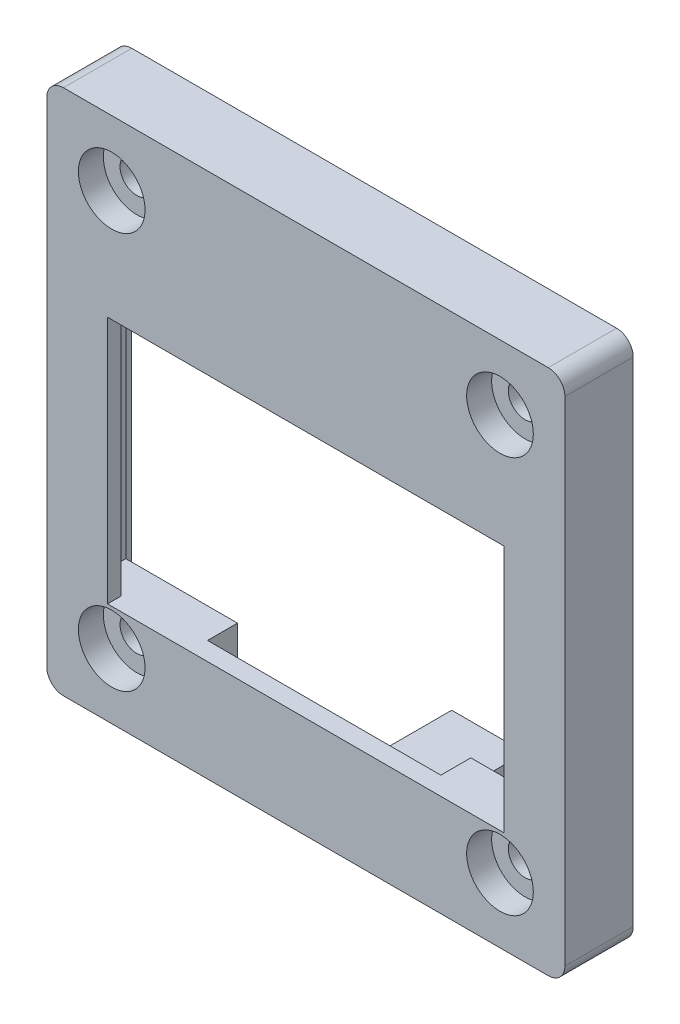
SolidWorks part; units mm, degrees
ref_plane "前视基准面" through (0, 0, 0) normal (0, 0, 1) x (1, 0, 0)
ref_plane "上视基准面" through (0, 0, 0) normal (0, 1, 0) x (1, 0, 0)
ref_plane "右视基准面" through (0, 0, 0) normal (1, 0, 0) x (0, 0, -1)
ref_plane "基准面1" through (0, 0, 12.2) normal (0, 0, 1) x (1, 0, 0)
sketch "草图1" plane through (0, 0, 12.2) normal (0, 0, 1) x (1, 0, 0)
  line L0 (28.2051, 1.8873) -> (-0.8873, 1.8873) construction
  line L1 (29.2051, -28.7131) -> (29.2051, 0.8873) construction
  line L2 (16.9238, -29.7131) -> (28.2051, -29.7131) construction
  line L3 (12.5103, -29.7131) -> (16.9238, -29.7131) construction
  line L4 (-0.8873, -29.7131) -> (12.5103, -29.7131) construction
  line L5 (-1.8873, 0.8873) -> (-1.8873, -28.7131) construction
  line L6 (28.2051, 1.8873) -> (-0.8873, 1.8873)
  line L7 (29.2051, -28.7131) -> (29.2051, 0.8873)
  line L8 (16.9238, -29.7131) -> (28.2051, -29.7131)
  line L9 (12.5103, -29.7131) -> (16.9238, -29.7131)
  line L10 (-0.8873, -29.7131) -> (12.5103, -29.7131)
  line L11 (-1.8873, 0.8873) -> (-1.8873, -28.7131)
  arc A0 (-0.8873, 1.8873) -> (-1.8873, 0.8873) centre (-0.8873, 0.8873) ccw construction
  arc A1 (29.2051, 0.8873) -> (28.2051, 1.8873) centre (28.2051, 0.8873) ccw construction
  arc A2 (28.2051, -29.7131) -> (29.2051, -28.7131) centre (28.2051, -28.7131) ccw construction
  arc A3 (-1.8873, -28.7131) -> (-0.8873, -29.7131) centre (-0.8873, -28.7131) ccw construction
  arc A4 (-0.8873, 1.8873) -> (-1.8873, 0.8873) centre (-0.8873, 0.8873) ccw
  arc A5 (29.2051, 0.8873) -> (28.2051, 1.8873) centre (28.2051, 0.8873) ccw
  arc A6 (28.2051, -29.7131) -> (29.2051, -28.7131) centre (28.2051, -28.7131) ccw
  arc A7 (-1.8873, -28.7131) -> (-0.8873, -29.7131) centre (-0.8873, -28.7131) ccw
extrude "凸台-拉伸1" add sketch "草图1" along normal blind 2.9
sketch "草图2" plane through (0, 0, 12.2) normal (0, 0, -1) x (-1, 0, 0)
  line L0 (-13.6589, -37.6912) -> (-13.6589, -51.7337) construction
  circle A0 centre (-2.0089, -25.8129) radius 0.9 construction
  circle A1 centre (-25.3089, -25.8129) radius 0.9 construction
  circle A2 centre (-25.3089, -2.0129) radius 0.95 construction
  circle A3 centre (-2.0089, -25.8129) radius 0.9 construction
  circle A4 centre (-25.3089, -25.8129) radius 0.9 construction
  circle A5 centre (-25.3089, -2.0129) radius 0.95 construction
  circle A6 centre (-25.3089, -2.0129) radius 1
  circle A7 centre (-25.3089, -25.8129) radius 1
  circle A8 centre (-2.0089, -25.8129) radius 1
  circle A9 centre (-2.0089, -2.0129) radius 1
  dimension "D1" = 2
  dimension "D2" = 2
  dimension "D3" = 2
extrude "切除-拉伸1" cut sketch "草图2" against normal up to next
sketch "草图3" plane through (0, 0, 12.2) normal (0, 0, -1) x (-1, 0, 0)
  line L4 (0.8873, 1.8873) -> (-28.2051, 1.8873)
  line L5 (-29.2051, 0.8873) -> (-29.2051, -28.7131)
  line L6 (-28.2051, -29.7131) -> (0.8873, -29.7131)
  line L7 (1.8873, -28.7131) -> (1.8873, 0.8873)
  line L8 (0.8873, 1.8873) -> (-28.2051, 1.8873)
  line L9 (-29.2051, 0.8873) -> (-29.2051, -28.7131)
  line L10 (-28.2051, -29.7131) -> (0.8873, -29.7131)
  line L11 (1.8873, -28.7131) -> (1.8873, 0.8873)
  line L16 (0.8873, 0.8873) -> (-28.2051, 0.8873)
  line L17 (-28.2051, 0.8873) -> (-28.2051, -28.7131)
  line L18 (-28.2051, -28.7131) -> (0.8873, -28.7131)
  line L19 (0.8873, -28.7131) -> (0.8873, 0.8873)
  line L20 (0.8873, 0.8873) -> (-28.2051, 0.8873)
  line L21 (-28.2051, 0.8873) -> (-28.2051, -28.7131)
  line L22 (-28.2051, -28.7131) -> (0.8873, -28.7131)
  line L23 (0.8873, -28.7131) -> (0.8873, 0.8873)
  arc A4 (-28.2051, 1.8873) -> (-29.2051, 0.8873) centre (-28.2051, 0.8873) ccw
  arc A5 (-29.2051, -28.7131) -> (-28.2051, -29.7131) centre (-28.2051, -28.7131) ccw
  arc A6 (0.8873, -29.7131) -> (1.8873, -28.7131) centre (0.8873, -28.7131) ccw
  arc A7 (1.8873, 0.8873) -> (0.8873, 1.8873) centre (0.8873, 0.8873) ccw
  arc A8 (-28.2051, 1.8873) -> (-29.2051, 0.8873) centre (-28.2051, 0.8873) ccw
  arc A9 (-29.2051, -28.7131) -> (-28.2051, -29.7131) centre (-28.2051, -28.7131) ccw
  arc A10 (0.8873, -29.7131) -> (1.8873, -28.7131) centre (0.8873, -28.7131) ccw
  arc A11 (1.8873, 0.8873) -> (0.8873, 1.8873) centre (0.8873, 0.8873) ccw
  dimension "D1" = 0
  dimension "D2" = 1
extrude "凸台-拉伸2" add sketch "草图3" along normal up to surface (1.2 mm away)
sketch "草图4" plane through (0, 0, 15.1) normal (0, 0, 1) x (1, 0, 0)
  line L0 (13.6589, -35.6153) -> (13.6589, -40.6693) construction
  line L1 (31.8185, -13.9129) -> (30.0348, -13.9129) construction
  line L4 (-0.0411, -4.2129) -> (27.3589, -4.2129)
  line L5 (-0.0411, -4.2129) -> (-0.0411, -23.6129)
  line L6 (-0.0411, -23.6129) -> (27.3589, -23.6129)
  line L7 (27.3589, -4.2129) -> (27.3589, -23.6129)
  line L8 (-0.0411, -4.2129) -> (27.3589, -23.6129) construction
  line L9 (-0.0411, -23.6129) -> (27.3589, -4.2129) construction
  point P3 (13.6589, -13.9129)
  dimension "D1" = 27.4
  dimension "D2" = 19.4
extrude "切除-拉伸2" cut sketch "草图4" against normal up to next
sketch "草图5" plane through (0, 0, 12.2) normal (0, 0, -1) x (-1, 0, 0)
  line L0 (-13.6589, 9.7796) -> (-13.6589, 5.4079) construction
  line L1 (0.8873, 0.8873) -> (-28.2051, 0.8873) construction
  line L2 (-20.6589, 0.8873) -> (-6.6589, 0.8873)
  line L3 (-20.6589, 0.8873) -> (-20.6589, -4.2129)
  line L4 (-20.6589, -4.2129) -> (-6.6589, -4.2129)
  line L5 (-6.6589, 0.8873) -> (-6.6589, -4.2129)
  line L6 (0.0411, -4.2129) -> (-27.3589, -4.2129) construction
  line L12 (-27.3589, -23.6129) -> (0.0411, -23.6129) construction
  line L15 (-20.6589, -23.6129) -> (-6.6589, -23.6129)
  line L16 (-20.6589, -23.6129) -> (-20.6589, -28.7131)
  line L17 (-20.6589, -28.7131) -> (-6.6589, -28.7131)
  line L18 (-6.6589, -23.6129) -> (-6.6589, -28.7131)
  line L19 (0.8873, -28.7131) -> (-28.2051, -28.7131) construction
  dimension "D1" = 14
  dimension "D2" = 14
extrude "切除-拉伸3" cut sketch "草图5" against normal blind 1.8
sketch "草图6" plane through (0, 0, 11) normal (0, 0, -1) x (-1, 0, 0)
  line L0 (-12.5103, -29.7131) -> (-16.9238, -29.7131) construction
  line L1 (-12.5103, -29.7131) -> (-16.9238, -29.7131)
  line L2 (0.8873, -28.7131) -> (-28.2051, -28.7131) construction
  line L3 (-16.9238, -29.7131) -> (-12.5103, -29.7131)
  line L4 (-16.9238, -29.7131) -> (-16.9238, -28.7131)
  line L5 (-16.9238, -28.7131) -> (-12.5103, -28.7131)
  line L6 (-12.5103, -29.7131) -> (-12.5103, -28.7131)
  line M4 (0.8873, -28.7131) -> (-28.2051, -28.7131)
  line M9 (-28.2051, -29.7131) -> (0.8873, -29.7131)
extrude "凸台-拉伸3" add sketch "草图6" along normal blind 5.8 contours L6 L4 M9 M4
sketch "草图8" plane through (0, -4.2129, 0) normal (0, 1, 0) x (1, 0, 0)
  line L0 (27.3589, -12.2) -> (27.3589, -15.1) construction
  line L1 (-0.0411, -15.1) -> (27.3589, -15.1)
  line L2 (-0.0411, -15.1) -> (-0.0411, -14)
  line L3 (-0.0411, -14) -> (27.3589, -14)
  line L4 (27.3589, -15.1) -> (27.3589, -14)
  line L5 (6.6589, -14) -> (20.6589, -14) construction
extrude "凸台-拉伸4" add sketch "草图8" against normal blind 4.5
sketch "草图9" plane through (0, 0, 15.1) normal (0, 0, 1) x (1, 0, 0)
  circle A0 centre (25.3089, -2.0129) radius 2
  circle A1 centre (2.0089, -2.0129) radius 2
  circle A2 centre (2.0089, -25.8129) radius 2
  circle A3 centre (25.3089, -25.8129) radius 2
  dimension "D1" = 4
extrude "切除-拉伸4" cut sketch "草图9" against normal blind 1.5
sketch "草图10" plane through (-0.0411, 0, 0) normal (1, 0, 0) x (0, 0, -1)
  line L0 (-14, -8.7129) -> (-15.1, -8.7129) construction
  line L1 (-15.1, -23.6129) -> (-14.3, -23.6129)
  line L2 (-15.1, -23.6129) -> (-15.1, -8.7129)
  line L3 (-15.1, -8.7129) -> (-14.3, -8.7129)
  line L4 (-14.3, -23.6129) -> (-14.3, -8.7129)
  dimension "D1" = 0.8
extrude "凸台-拉伸5" add sketch "草图10" along normal blind 1.8
ref_plane "基准面2" through (13.6589, 0, 0) normal (1, 0, 0) x (0, 0, -1)
mirror "镜向1" about plane through (13.6589, 0, 0) normal (1, 0, 0) of "凸台-拉伸5"
